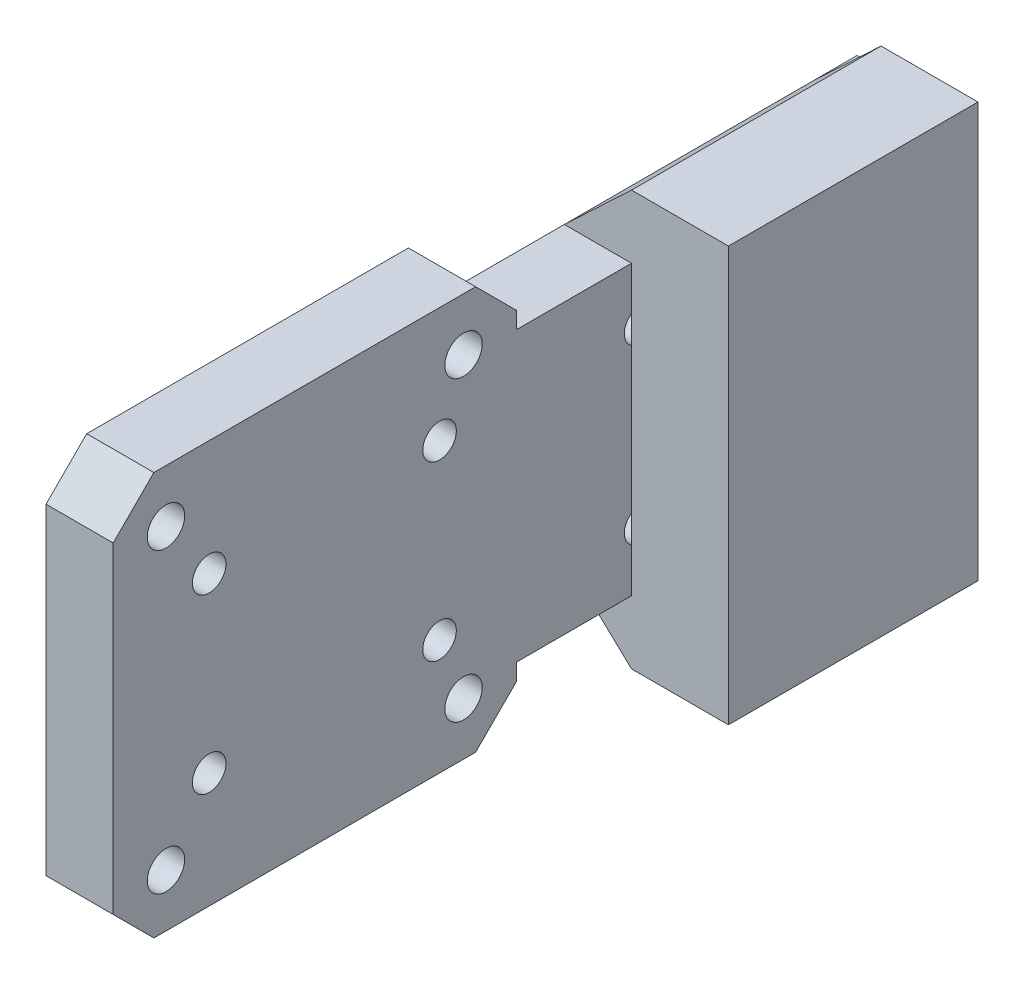
SolidWorks part; units mm, degrees
ref_plane "Front Plane" through (0, 0, 0) normal (0, 0, 1) x (1, 0, 0)
ref_plane "Top Plane" through (0, 0, 0) normal (0, 1, 0) x (1, 0, 0)
ref_plane "Right Plane" through (0, 0, 0) normal (1, 0, 0) x (0, 0, -1)
sketch "Sketch2" plane through (0, 0, 0) normal (1, 0, 0) x (0, 0, -1)
  line L1 (13, 21.6) -> (-13, 21.6)
  line L2 (13, 21.6) -> (13, -21.6)
  line L3 (13, -21.6) -> (-13, -21.6)
  line L4 (-13, 21.6) -> (-13, -21.6)
  line L5 (13, 21.6) -> (-13, -21.6) construction
  line L6 (13, -21.6) -> (-13, 21.6) construction
  point P0 (0, 0)
  dimension "D1" = 26
  dimension "D2" = 43.2
extrude "Boss-Extrude1" add sketch "Sketch2" along normal blind 10.1
sketch "Sketch3" plane through (0, 0, 0) normal (-1, 0, 0) x (0, 0, 1)
  line L0 (27.5, 15) -> (27.5, -15) construction
  line L1 (-12, 9) -> (12, 9) construction
  line L2 (-12, 9) -> (-12, -9) construction
  line L3 (-12, -9) -> (12, -9) construction
  line L4 (12, 9) -> (12, -9) construction
  line L5 (-12, 9) -> (12, -9) construction
  line L6 (-12, -9) -> (12, 9) construction
  line L7 (-17.5, 15) -> (17.5, 15)
  line L8 (-17.5, 15) -> (-17.5, -15)
  line L9 (-17.5, -15) -> (17.5, -15)
  line L10 (17.5, 15) -> (17.5, -15) construction
  line L11 (-17.5, 15) -> (17.5, -15) construction
  line L12 (-17.5, -15) -> (17.5, 15) construction
  line L13 (17.5, 15) -> (62.5, 15)
  line L14 (17.5, 15) -> (17.5, -15) construction
  line L15 (17.5, -15) -> (62.5, -15)
  line L16 (62.5, 15) -> (62.5, -15)
  line L17 (27.5, 0) -> (17.5, 0) construction
  line L18 (22.5, 0) -> (22.5, -15) construction
  circle A0 centre (12, 9) radius 1.75
  circle A1 centre (12, -9) radius 1.75
  circle A2 centre (-12, -9) radius 1.75
  circle A3 centre (-12, 9) radius 1.75
  circle A4 centre (57, -9) radius 1.75
  circle A5 centre (57, 9) radius 1.75
  circle A6 centre (33, -9) radius 1.75
  circle A7 centre (33, 9) radius 1.75
  point P0 (0, 0)
  point P5 (0, 0)
  dimension "D1" = 24
  dimension "D5" = 3.5
  dimension "D2" = 18
  dimension "D3" = 35
  dimension "D4" = 30
  dimension "D6" = 45
  dimension "D7" = 35
extrude "Boss-Extrude2" add sketch "Sketch3" along normal blind 7
sketch "Sketch4" plane through (-7, 0, 0) normal (-1, 0, 0) x (0, 0, 1)
  line L0 (62.5, 12) -> (36.5, 12)
  line L1 (62.5, -15) -> (62.5, 15) construction
  line L2 (62.5, 15) -> (-17.5, 15) construction
  line L3 (62.5, 12) -> (62.5, 15)
  line L4 (62.5, 15) -> (33.5, 15)
  arc A0 (36.5, 12) -> (33.5, 15) centre (36.5, 15) cw
  dimension "D1" = 26
  dimension "D2" = 3
extrude "Cut-Extrude1" [suppressed] cut sketch "Sketch4" against normal through all contours L0 A0 L4 L3
sketch "Sketch5" plane through (0, 0, -13) normal (0, 0, -1) x (-1, 0, 0)
  line L0 (0, -21.6) -> (0, -15) construction
  line L1 (7, -15) -> (0, -15) construction
  line L2 (7, 15) -> (0, 15) construction
  line L3 (0, 15) -> (0, 21.6) construction
  line L4 (0, -21.6) -> (0, -15)
  line L5 (7, -15) -> (0, -15)
  line L6 (7, 15) -> (0, 15)
  line L7 (0, 15) -> (0, 21.6)
  line L8 (0, 21.6) -> (7, 15)
  line L9 (7, -15) -> (0, -21.6)
extrude "Boss-Extrude3" add sketch "Sketch5" against normal up to surface (26 mm away) up to face at (2.02, 0, 13)
sketch "Sketch7" plane through (-7, 0, 0) normal (-1, 0, 0) x (0, 0, 1)
  line L0 (62.5, -15) -> (62.5, 15) construction
  line L1 (67, 21) -> (25, 21)
  line L2 (67, 21) -> (67, -21)
  line L3 (67, -21) -> (25, -21)
  line L4 (25, 21) -> (25, 15)
  line L5 (67, 21) -> (25, -21) construction
  line L6 (67, -21) -> (25, 21) construction
  line L8 (25, -15) -> (25, -21)
  line L16 (-17.5, -15) -> (-13, -15)
  line L17 (-13, -15) -> (13, -15)
  line L18 (13, -15) -> (62.5, -15)
  line L19 (62.5, -15) -> (62.5, 15)
  line L20 (62.5, 15) -> (13, 15)
  line L21 (13, 15) -> (-13, 15)
  line L22 (-13, 15) -> (-17.5, 15)
  line L23 (-17.5, 15) -> (-17.5, -15)
  line L24 (-17.5, -15) -> (-13, -15)
  line L26 (25, -15) -> (62.5, -15)
  line L27 (62.5, -15) -> (62.5, 15)
  line L28 (62.5, 15) -> (25, 15)
  line L30 (-13, 15) -> (-17.5, 15)
  line L31 (-17.5, 15) -> (-17.5, -15)
  point P0 (46, 0)
  point P5 (50.3425, 0)
  point P8 (62.5, 0)
  point P9 (67.2798, 21)
  line M14 (13, -15) -> (62.5, -15)
  line M15 (62.5, -15) -> (62.5, 15)
  line M16 (62.5, 15) -> (13, 15)
  dimension "D1" = 42
  dimension "D2" = 4.5
  dimension "D3" = 0
extrude "Boss-Extrude4" add sketch "Sketch7" against normal up to surface (7 mm away) contours L8 L3 L2 L1 L4 M14 M16 M15 up to face at (0, 9, 31.25)
chamfer "Chamfer1" distance 4.24 angle 45 4 edges at (-3.5, 21, 25) (-3.5, -21, 25) (-3.5, -21, 67) (-3.5, 21, 67)
sketch "StepperScrewPattern" plane through (-7, 0, 0) normal (-1, 0, 0) x (0, 0, 1)
  line L0 (46, 21) -> (46, -21) construction
  line L1 (62.76, 21) -> (29.24, 21) construction
  line L2 (62.76, -21) -> (29.24, -21) construction
  line L4 (30.5, 15.5) -> (61.5, 15.5) construction
  line L5 (30.5, 15.5) -> (30.5, -15.5) construction
  line L6 (30.5, -15.5) -> (61.5, -15.5) construction
  line L7 (61.5, 15.5) -> (61.5, -15.5) construction
  line L8 (30.5, 15.5) -> (61.5, -15.5) construction
  line L9 (30.5, -15.5) -> (61.5, 15.5) construction
  point P6 (46, 0)
  dimension "D1" = 31
hole_wizard "CBORE for M5 Hex Head Cap Screw1" positions "Sketch11" profile "Sketch13" counterbore size "M5" standard "ANSI Metric" end condition through all
sketch "Sketch11" plane through (-7, 0, 0) normal (-1, 0, 0) x (0, 0, 1)
  point P0 (61.5, 15.5)
  point P3 (61.5, -15.5)
  point P6 (30.5, -15.5)
  point P9 (30.5, 15.5)
sketch "Sketch13" plane through (-7, 15.5, 61.5) normal (0, 1, 0) x (0, 0, 1)
  line L0 (0, 0) -> (0, 17.1)
  line L1 (0, 17.1) -> (1.95, 17.1)
  line L3 (1.95, 17.1) -> (1.95, 4)
  line L4 (1.95, 4) -> (3, 4)
  line L5 (3, 4) -> (3, 0)
  line L7 (3, 0) -> (0, 0)
  line L11 (0, -6.35) -> (0, 107.95) construction
  dimension "Thru Hole Dia." = 3.9
  dimension "Thru Hole Depth" = 17.1
  dimension "C'Bore Dia." = 6
  dimension "C'Bore Depth" = 4
